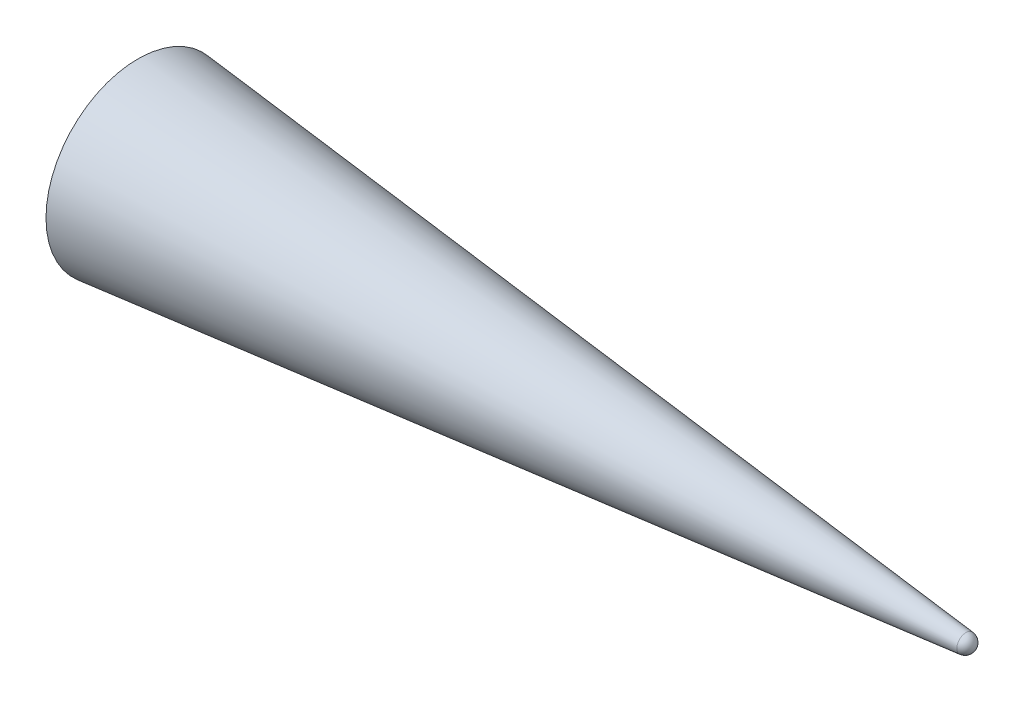
SolidWorks part; units mm, degrees
ref_plane "Front Plane" through (0, 0, 0) normal (0, 0, 1) x (1, 0, 0)
ref_plane "Top Plane" through (0, 0, 0) normal (0, 1, 0) x (1, 0, 0)
ref_plane "Right Plane" through (0, 0, 0) normal (1, 0, 0) x (0, 0, -1)
sketch "Sketch1" plane through (0, 0, 0) normal (0, 1, 0) x (1, 0, 0)
  line L0 (900.9901, 9.901) -> (0, 100)
  line L1 (0, 0) -> (909.9504, 0)
  line L2 (0, 0) -> (0, 100)
  arc A0 (909.9504, 0) -> (900.9901, 9.901) centre (900, 0) ccw
  dimension "D1" = 100
  dimension "D3" = 900
revolve "Revolve2" add sketch "Sketch1" angle 360 about L1
